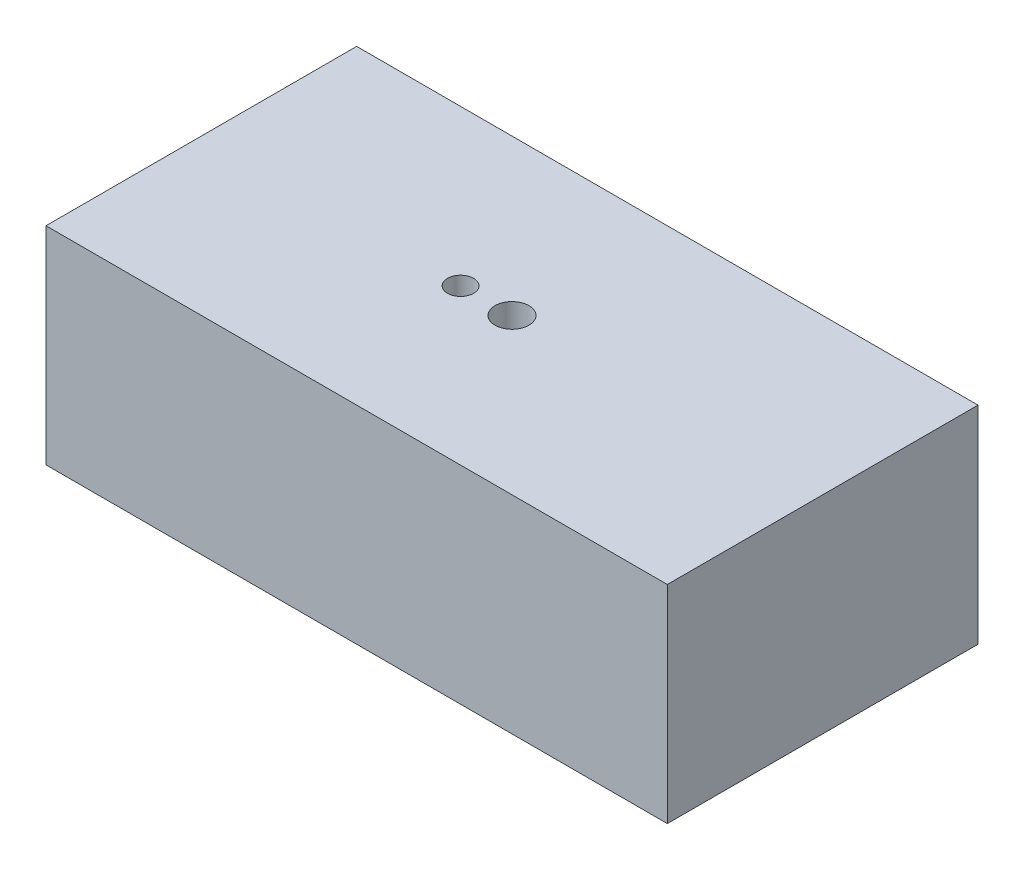
SolidWorks part; units mm, degrees
ref_plane "Front Plane" through (0, 0, 0) normal (0, 0, 1) x (1, 0, 0)
ref_plane "Top Plane" through (0, 0, 0) normal (0, 1, 0) x (1, 0, 0)
ref_plane "Right Plane" through (0, 0, 0) normal (1, 0, 0) x (0, 0, -1)
sketch "Sketch1" plane through (0, 0, 0) normal (0, 1, 0) x (1, 0, 0)
  line L0 (5.4847, -0.0047) -> (-9.5153, -0.0047) construction
  line L1 (-15, -7.5) -> (15, -7.5)
  line L2 (-15, -7.5) -> (-15, 7.5)
  line L3 (-15, 7.5) -> (15, 7.5)
  line L4 (15, -7.5) -> (15, 7.5)
  line L5 (0, 0) -> (0, 7.5) construction
  circle A0 centre (0, 0) radius 0.82
  circle A1 centre (-2.48, -0.0047) radius 0.63
  dimension "D3" = 1.64
  dimension "D4" = 2.48
  dimension "D6" = 1.26
  dimension "D1" = 30
  dimension "D2" = 15
extrude "Boss-Extrude1" add sketch "Sketch1" along normal blind 10
